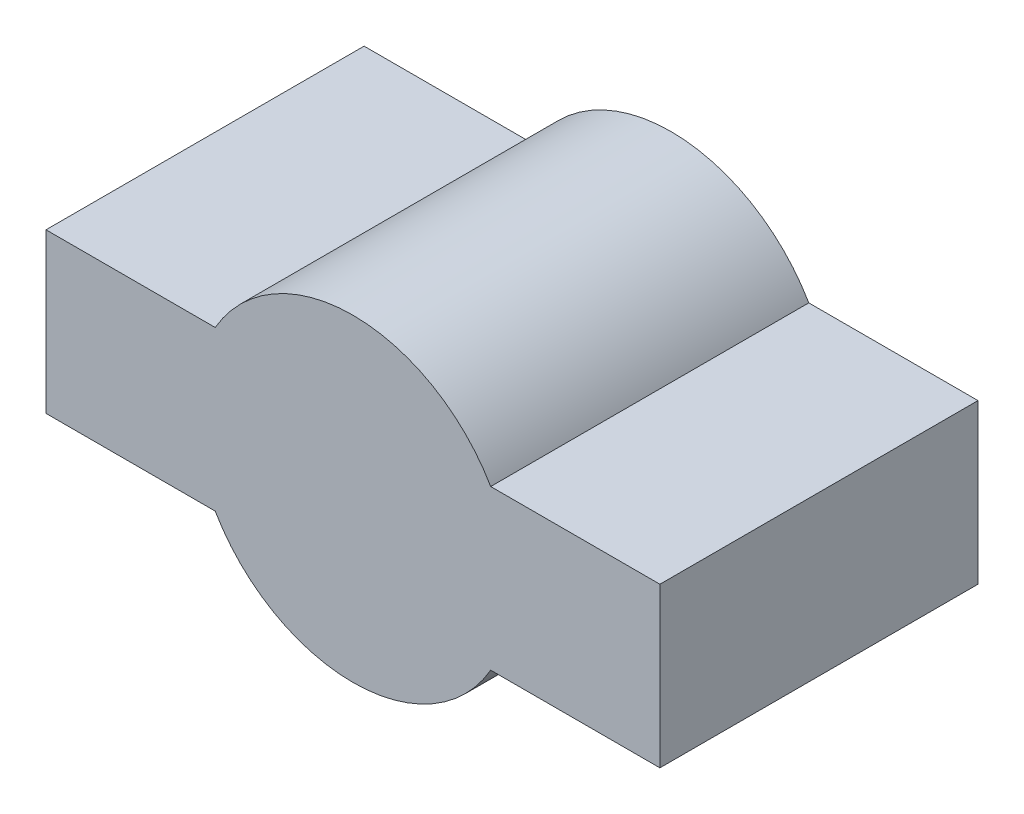
SolidWorks part; units mm, degrees
material "Chrome Stainless Steel"
ref_plane "Front Plane" through (0, 0, 0) normal (0, 0, 1) x (1, 0, 0)
ref_plane "Top Plane" through (0, 0, 0) normal (0, 1, 0) x (1, 0, 0)
ref_plane "Right Plane" through (0, 0, 0) normal (1, 0, 0) x (0, 0, -1)
sketch "Sketch1" plane through (0, 0, 0) normal (0, 0, 1) x (1, 0, 0)
  line L0 (0.866, 0.5) -> (1.93, 0.5)
  line L1 (-1.93, 0.5) -> (-0.866, 0.5)
  line L2 (-1.93, 0.5) -> (-1.93, -0.5)
  line L3 (-1.93, -0.5) -> (-0.866, -0.5)
  line L4 (1.93, 0.5) -> (1.93, -0.5)
  line L5 (-1.93, 0.5) -> (1.93, -0.5) construction
  line L6 (-1.93, -0.5) -> (1.93, 0.5) construction
  line L7 (0.866, -0.5) -> (1.93, -0.5)
  arc A0 (-0.866, -0.5) -> (0.866, -0.5) centre (0, 0) ccw
  arc A1 (0.866, 0.5) -> (-0.866, 0.5) centre (0, 0) ccw
  dimension "D1" = 1
  dimension "D2" = 1
  dimension "D3" = 3.86
extrude "Boss-Extrude1" add sketch "Sketch1" along normal blind 2
sketch "Sketch2" plane through (0, 0, 0) normal (0, 0, -1) x (-1, 0, 0)
  circle A0 centre (0, 0) radius 0.95
  dimension "D1" = 1.9
extrude "Cut-Extrude1" cut sketch "Sketch2" against normal blind 1.8
cosmetic thread "Cosmetic Thread1" parameters "D2"=2.5
